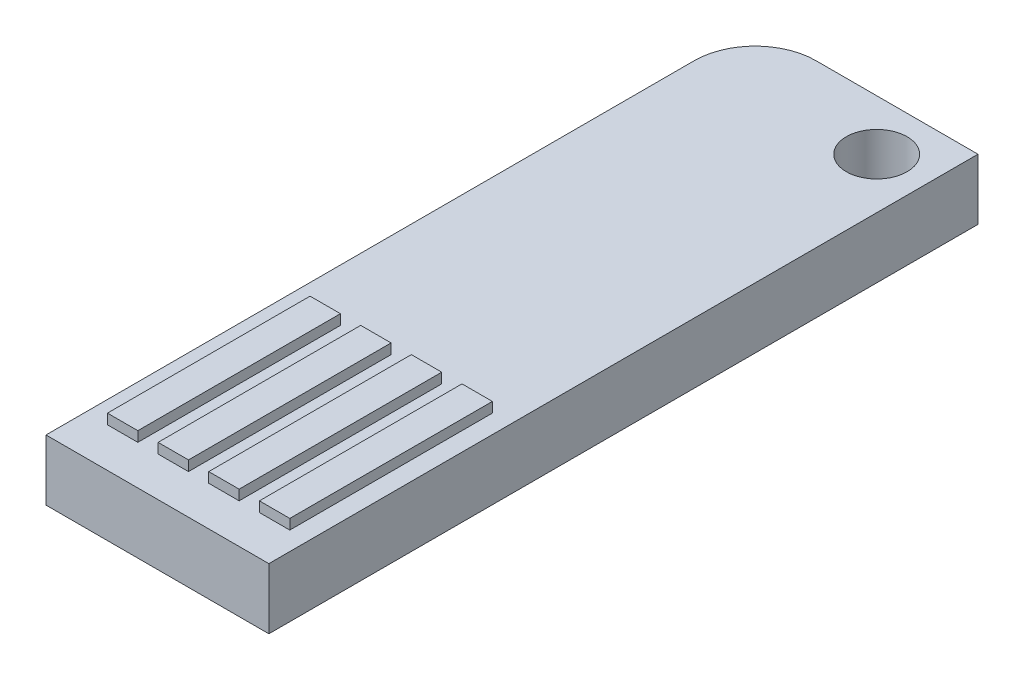
SolidWorks part; units mm, degrees
ref_plane "Front Plane" through (0, 0, 0) normal (0, 0, 1) x (1, 0, 0)
ref_plane "Top Plane" through (0, 0, 0) normal (0, 1, 0) x (1, 0, 0)
ref_plane "Right Plane" through (0, 0, 0) normal (1, 0, 0) x (0, 0, -1)
sketch "Sketch1" plane through (0, 0, 0) normal (0, 1, 0) x (1, 0, 0)
  line L1 (-5.5, 17.5) -> (5.5, 17.5)
  line L2 (-5.5, 17.5) -> (-5.5, -17.5)
  line L3 (-5.5, -17.5) -> (5.5, -17.5)
  line L4 (5.5, 17.5) -> (5.5, -17.5)
  line L5 (-5.5, 17.5) -> (5.5, -17.5) construction
  line L6 (-5.5, -17.5) -> (5.5, 17.5) construction
  point P0 (0, 0)
  dimension "D1" = 11
  dimension "D2" = 35
extrude "Boss-Extrude1" add sketch "Sketch1" along normal blind 3
sketch "Sketch2" plane through (0, 3, 0) normal (0, 1, 0) x (1, 0, 0)
  circle A0 centre (3, 15) radius 1.5
  dimension "D1" = 3
extrude "Cut-Extrude1" cut sketch "Sketch2" against normal blind 3
fillet "Fillet1" radius 3 1 edges at (-5.5, 1.5, -17.5)
sketch "Sketch3" plane through (0, 3, 0) normal (0, 1, 0) x (1, 0, 0)
  line L0 (-1.9175, -5.5501) -> (-1.9175, -15.5501)
  line L1 (-4.4175, -5.5501) -> (-2.9175, -5.5501)
  line L2 (-4.4175, -5.5501) -> (-4.4175, -15.5501)
  line L3 (-4.4175, -15.5501) -> (-2.9175, -15.5501)
  line L4 (-2.9175, -5.5501) -> (-2.9175, -15.5501)
  line L5 (-4.4175, -5.5501) -> (-2.9175, -15.5501) construction
  line L6 (-4.4175, -15.5501) -> (-2.9175, -5.5501) construction
  line L7 (-1.9175, -5.5501) -> (-0.4175, -5.5501)
  line L8 (-0.4175, -5.5501) -> (-0.4175, -15.5501)
  line L9 (-1.9175, -15.5501) -> (-0.4175, -15.5501)
  line L10 (0.5825, -5.5501) -> (0.5825, -15.5501)
  line L11 (0.5825, -5.5501) -> (2.0825, -5.5501)
  line L12 (2.0825, -5.5501) -> (2.0825, -15.5501)
  line L13 (0.5825, -15.5501) -> (2.0825, -15.5501)
  line L14 (3.0825, -5.5501) -> (3.0825, -15.5501)
  line L15 (3.0825, -5.5501) -> (4.5825, -5.5501)
  line L16 (4.5825, -5.5501) -> (4.5825, -15.5501)
  line L17 (3.0825, -15.5501) -> (4.5825, -15.5501)
  point P0 (0, -35)
  point P7 (2.5, -35)
  point P12 (5, -35)
  point P17 (7.5, -35)
  dimension "D1" = 1.5
  dimension "D2" = 10
  dimension "D3" = 4
extrude "Boss-Extrude2" add sketch "Sketch3" along normal blind 0.5
